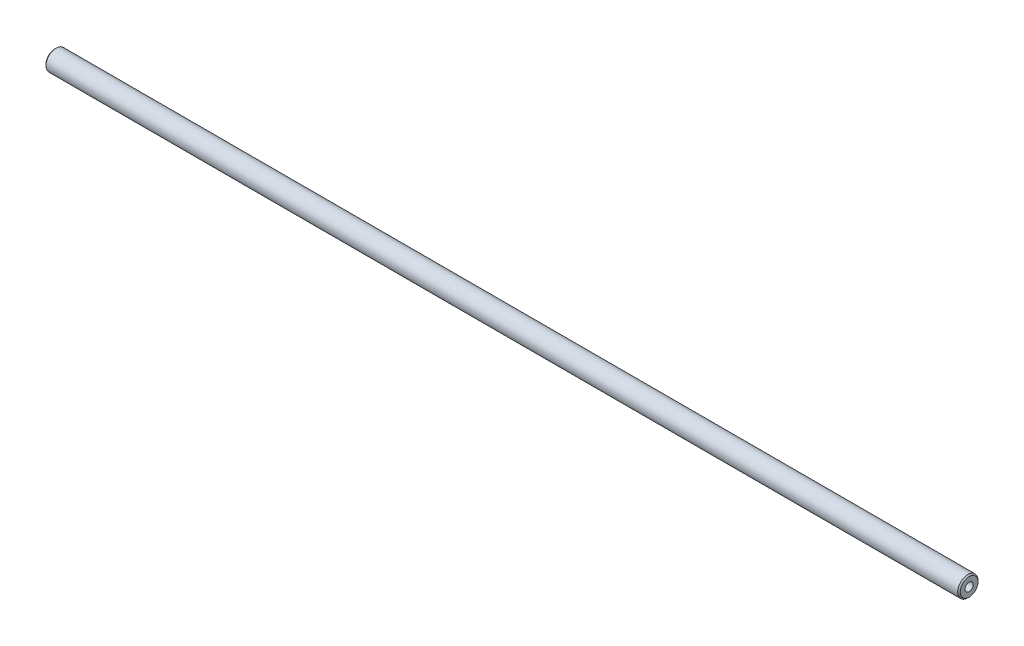
SolidWorks part; units mm, degrees
ref_plane "Front" through (0, 0, 0) normal (0, 0, 1) x (1, 0, 0)
ref_plane "Top" through (0, 0, 0) normal (0, 1, 0) x (1, 0, 0)
ref_plane "Right" through (0, 0, 0) normal (1, 0, 0) x (0, 0, -1)
ref_plane "Plane1" through (-180, 0, 0) normal (-1, 0, 0) x (0, -1, 0)
sketch "Sketch1" plane through (0, 0, 0) normal (-1, 0, 0) x (0, -1, 0)
  circle A0 centre (0, 0) radius 4
  dimension "D1" = 8
extrude "Boss-Extrude1" add sketch "Sketch1" against normal mid plane 360
hole_wizard "M3 Clearance Hole1" positions "Sketch3" profile "Sketch2" hole size "M3" standard "ANSI Metric"
sketch "Sketch3" plane through (180, 0, 0) normal (1, 0, 0) x (0, 0, -1)
  point P0 (0, 0)
sketch "Sketch2" plane through (180, 0, 0) normal (0, 1, 0) x (0, 0, -1)
  line L0 (0, 0) -> (0, 15.974)
  line L1 (0, 15.974) -> (1.621, 15)
  line L2 (1.621, 15) -> (1.621, 0)
  line L5 (1.621, 0) -> (0, 0)
  line L10 (0, 15.974) -> (-1.621, 15) construction
  line L11 (0, -6.35) -> (0, 107.95) construction
  dimension "Hole Dia." = 3.242
  dimension "Hole Depth" = 15
  dimension "Drill Angle" = 118
hole_wizard "M3 Clearance Hole2" positions "Sketch5" profile "Sketch4" hole size "M3" standard "ANSI Metric"
sketch "Sketch5" plane through (-180, 0, 0) normal (-1, 0, 0) x (0, 0, 1)
  point P0 (0, 0)
sketch "Sketch4" plane through (-180, 0, 0) normal (0, 1, 0) x (0, 0, 1)
  line L0 (0, 0) -> (0, 15.974)
  line L1 (0, 15.974) -> (1.621, 15)
  line L2 (1.621, 15) -> (1.621, 0)
  line L5 (1.621, 0) -> (0, 0)
  line L10 (0, 15.974) -> (-1.621, 15) construction
  line L11 (0, -6.35) -> (0, 107.95) construction
  dimension "Hole Dia." = 3.242
  dimension "Hole Depth" = 15
  dimension "Drill Angle" = 118
chamfer "Chamfer1" distance 0.5 angle 45 2 edges at (-180, 0, -4) (180, 0, -4)
